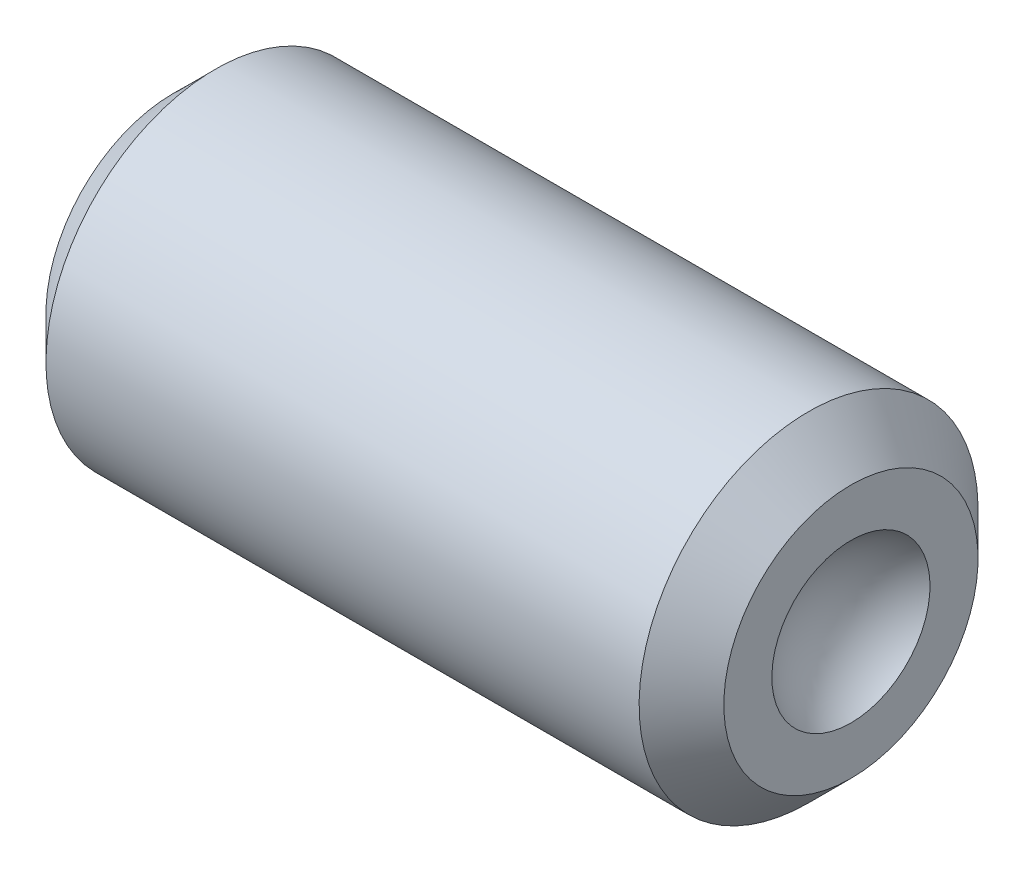
SolidWorks part; units mm, degrees
ref_plane "Front Plane" through (0, 0, 0) normal (0, 0, 1) x (1, 0, 0)
ref_plane "Top Plane" through (0, 0, 0) normal (0, 1, 0) x (1, 0, 0)
ref_plane "Right Plane" through (0, 0, 0) normal (1, 0, 0) x (0, 0, -1)
sketch "Sketch1" plane through (0, 0, 0) normal (0, 0, 1) x (1, 0, 0)
  line L0 (0, 0) -> (0, 1.125)
  line L1 (0, 1.125) -> (0.375, 1.5)
  line L2 (0.375, 1.5) -> (5.625, 1.5)
  line L3 (5.625, 1.5) -> (6, 1.125)
  line L4 (0, 0) -> (5.625, 0) construction
  line L5 (0.375, 1.5) -> (0.375, 1.125) construction
  line L6 (0.375, 1.125) -> (0.375, 0.75) construction
  line L7 (0.375, 0.75) -> (0.375, 0.375) construction
  line L8 (0.375, 0.375) -> (0.375, 0) construction
  line L9 (0.375, 1.125) -> (0, 1.125) construction
  line L10 (5.625, 1.5) -> (5.625, 0) construction
  line L11 (6, 1.125) -> (6, 0.7)
  line L12 (0, 0) -> (5.625, 0)
  arc A0 (5.625, 0) -> (6, 0.7) centre (6.4658, 0) cw
  dimension "D1" = 45
  dimension "D2" = 3
  dimension "D3" = 6
  dimension "D4" = 1.4
revolve "Revolve1" add sketch "Sketch1" angle 360 about L12
sketch "Sketch2" plane through (0, 0, 0) normal (-1, 0, 0) x (0, 0, 1)
  line L1 (0, 0.866) -> (-0.75, 0.433)
  line L2 (-0.75, 0.433) -> (-0.75, -0.433)
  line L3 (-0.75, -0.433) -> (0, -0.866)
  line L4 (0, -0.866) -> (0.75, -0.433)
  line L5 (0.75, -0.433) -> (0.75, 0.433)
  line L6 (0.75, 0.433) -> (0, 0.866)
  circle A0 centre (0, 0) radius 0.75 construction
  dimension "D1" = 1.5
extrude "Cut-Extrude1" cut sketch "Sketch2" against normal offset from surface (4 mm away) 2 up to face at (6, -1.125, 0)
